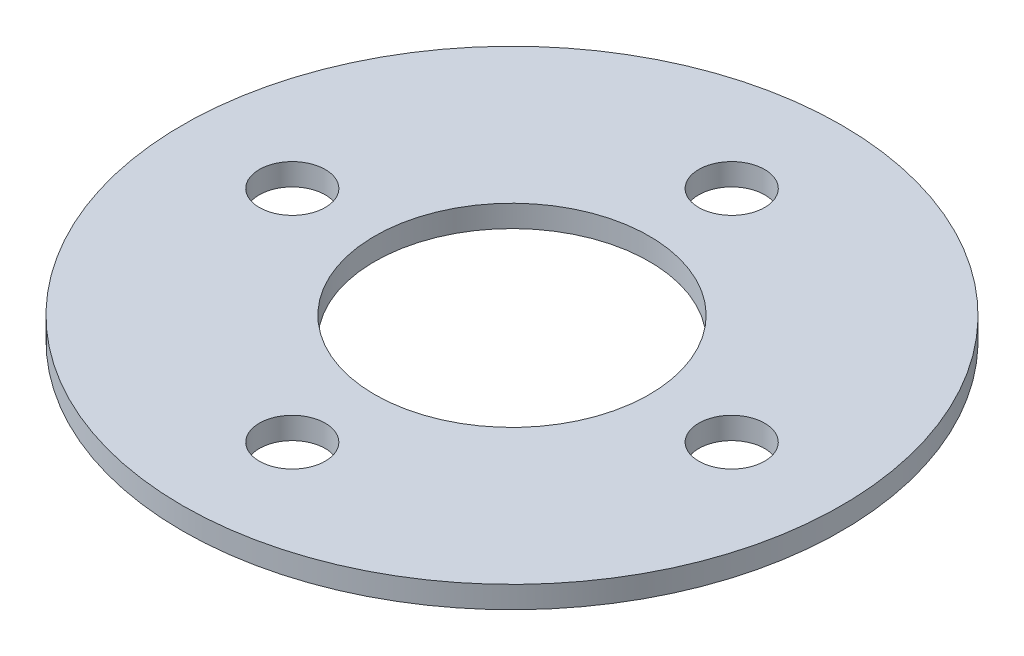
SolidWorks part; units mm, degrees
ref_plane "前视基准面" through (0, 0, 0) normal (0, 0, 1) x (1, 0, 0)
ref_plane "上视基准面" through (0, 0, 0) normal (0, 1, 0) x (1, 0, 0)
ref_plane "右视基准面" through (0, 0, 0) normal (1, 0, 0) x (0, 0, -1)
other "Configuration Table"
sketch "草图1" plane through (0, 0, 0) normal (0, 1, 0) x (1, 0, 0)
  circle A0 centre (0, 0) radius 15
  circle A1 centre (0, 0) radius 6.25
  circle A2 centre (0, 10) radius 1.5
  circle A3 centre (10, 0) radius 1.5
  circle A4 centre (0, -10) radius 1.5
  circle A5 centre (-10, 0) radius 1.5
  point P15 (0, 0)
  dimension "D1" = 30
  dimension "D2" = 12.5
  dimension "D4" = 3
  dimension "D3" = 10
  dimension "D5" = 4
extrude "凸台-拉伸1" add sketch "草图1" along normal blind 1
